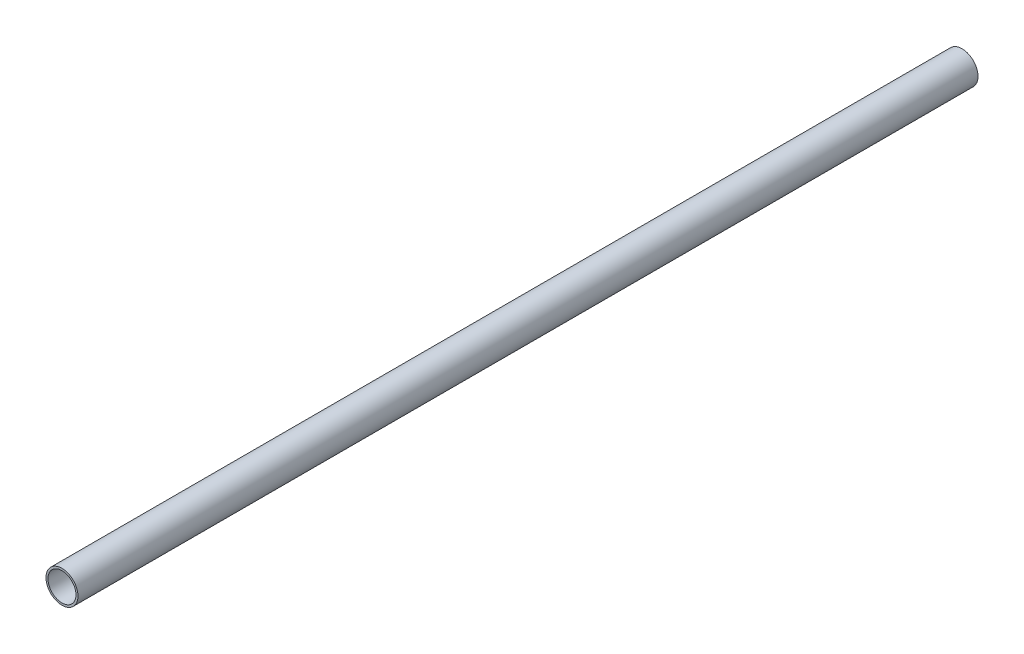
SolidWorks part; units mm, degrees
ref_plane "Front Plane" through (0, 0, 0) normal (0, 0, 1) x (1, 0, 0)
ref_plane "Top Plane" through (0, 0, 0) normal (0, 1, 0) x (1, 0, 0)
ref_plane "Right Plane" through (0, 0, 0) normal (1, 0, 0) x (0, 0, -1)
sketch "Sketch1" plane through (0, 0, 0) normal (0, 0, 1) x (1, 0, 0)
  circle A0 centre (0, 0) radius 7
extrude "Extrude-Thin1" add sketch "Sketch1" along normal blind 450 thin
